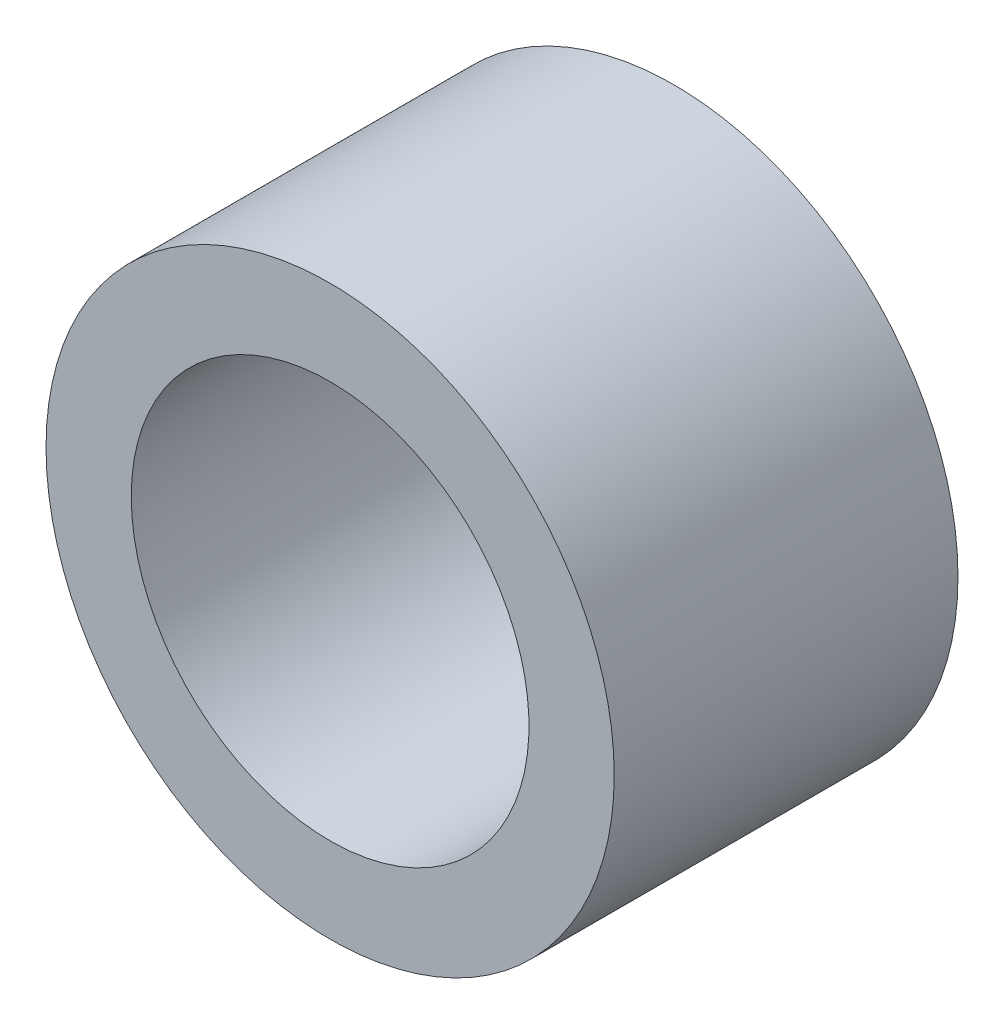
SolidWorks part; units mm, degrees
ref_plane "Piano frontale" through (0, 0, 0) normal (0, 0, 1) x (1, 0, 0)
ref_plane "Piano superiore" through (0, 0, 0) normal (0, 1, 0) x (1, 0, 0)
ref_plane "Piano destro" through (0, 0, 0) normal (1, 0, 0) x (0, 0, -1)
sketch "Schizzo1" plane through (0, 0, 0) normal (0, 0, 1) x (1, 0, 0)
  circle A0 centre (0, 0) radius 70
  circle A1 centre (0, 0) radius 100
  dimension "D1" = 140
  dimension "D2" = 200
extrude "Estrusione-Estrusione1" add sketch "Schizzo1" along normal blind 121
